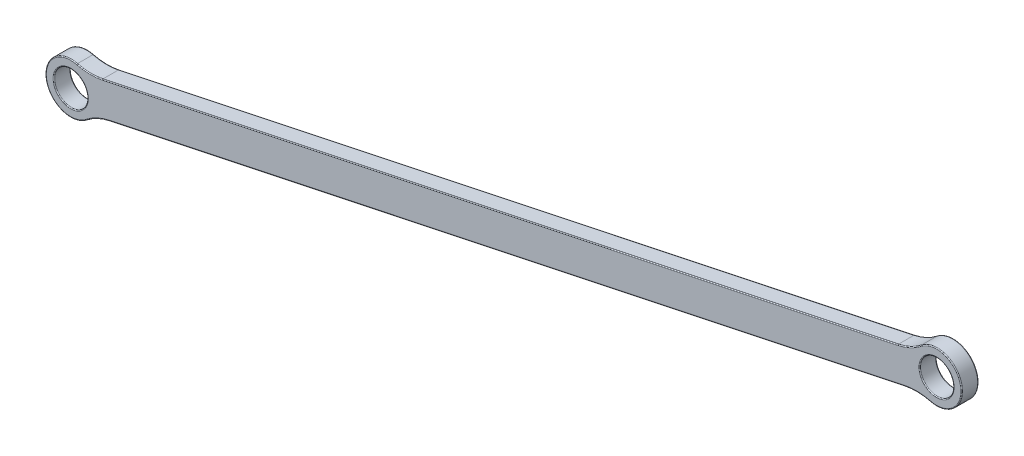
SolidWorks part; units mm, degrees
ref_plane "Front Plane" through (0, 0, 0) normal (0, 0, 1) x (1, 0, 0)
ref_plane "Top Plane" through (0, 0, 0) normal (0, 1, 0) x (1, 0, 0)
ref_plane "Right Plane" through (0, 0, 0) normal (1, 0, 0) x (0, 0, -1)
sketch "Sketch1" plane through (0, 0, 0) normal (0, 0, 1) x (1, 0, 0)
  line L0 (-55.6926, 229.8367) -> (-210.4552, 197.1426) construction
  line L1 (-55.6926, 229.8367) -> (-210.4552, 197.1426) construction
  line L2 (-210.4552, 197.1426) -> (-55.6926, 229.8367) construction
  line L3 (-211.0753, 200.0779) -> (-56.3127, 232.772)
  line L4 (-209.8351, 194.2074) -> (-55.0725, 226.9015)
  arc A0 (-211.0753, 200.0779) -> (-209.8351, 194.2074) centre (-210.4552, 197.1426) ccw
  arc A1 (-55.0725, 226.9015) -> (-56.3127, 232.772) centre (-55.6926, 229.8367) ccw
  circle A2 centre (-210.4552, 197.1426) radius 4.5
  circle A3 centre (-55.6926, 229.8367) radius 4.5
  arc A4 (-211.0753, 200.0779) -> (-209.8351, 194.2074) centre (-210.4552, 197.1426) cw
  arc A5 (-56.3127, 232.772) -> (-55.0725, 226.9015) centre (-55.6926, 229.8367) ccw
  point P3 (-133.0739, 213.4897)
  dimension "D2" = 9
  dimension "D1" = 6
  dimension "D3" = 158.1783
extrude "Boss-Extrude1" add sketch "Sketch1" against normal blind 3 contours L3 A2 L4 A0 | L3 A4 L4 A2 | A3 L3 A2 L4 | L4 A3 L3 A1 | A5 L3 A3 L4
fillet "Fillet1" radius 10 4 edges at (-59.5943, 232.0787, -1.5) (-58.3542, 226.2083, -1.5) (-206.5535, 194.9007, -1.5) (-207.7936, 200.7711, -1.5)
fillet "Fillet2" radius 0.15 20 edges at (-207.4552, 197.1426, -3) (-207.4552, 197.1426, 0) (-205.7222, 194.8084, -3) (-205.7222, 194.8084, 0) (-132.4538, 210.5545, -3) (-132.4538, 210.5545, 0) (-59.0771, 225.7877, -3) (-59.0771, 225.7877, 0) (-51.2898, 230.7669, -3) (-51.2898, 230.7669, 0) (-60.4256, 232.1709, -3) (-60.4256, 232.1709, 0) (-133.694, 216.4249, 0) (-133.694, 216.4249, -3) (-207.0707, 201.1917, -3) (-207.0707, 201.1917, 0) (-214.858, 196.2125, -3) (-214.858, 196.2125, 0) (-52.6926, 229.8367, -3) (-52.6926, 229.8367, 0)
